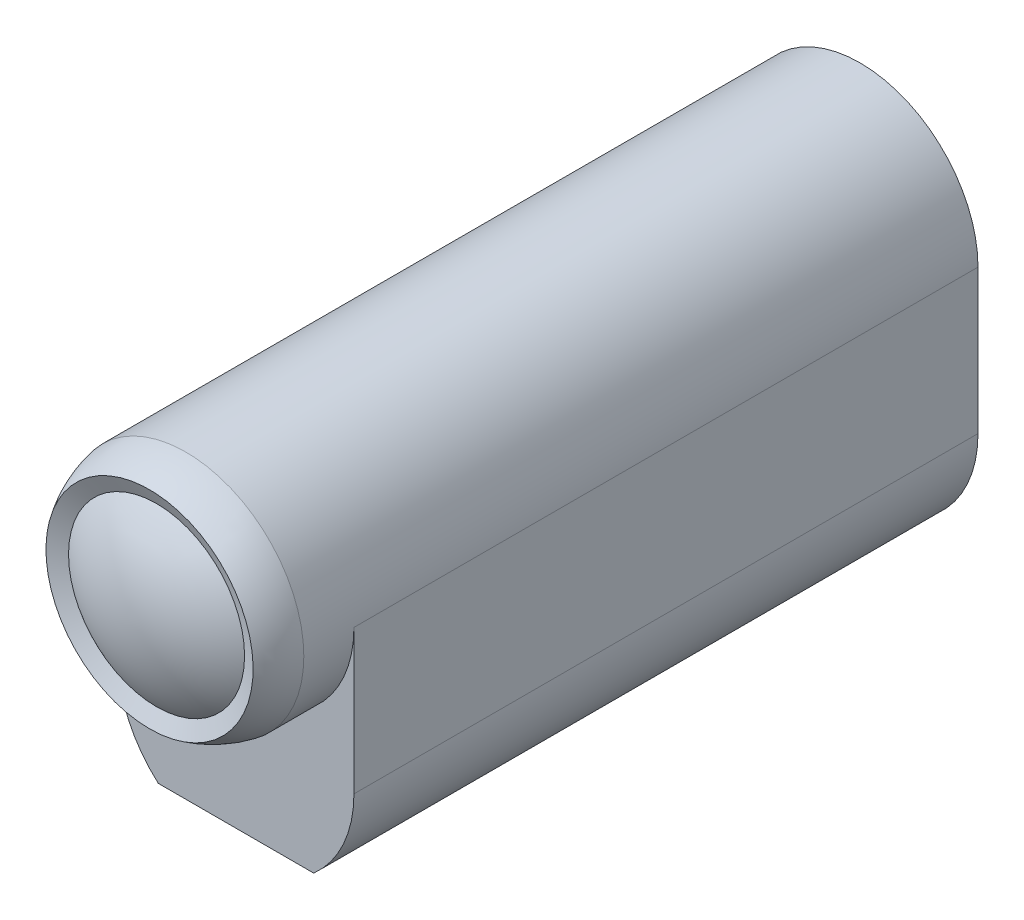
SolidWorks part; units mm, degrees
ref_plane "Front" through (0, 0, 0) normal (0, 0, 1) x (1, 0, 0)
ref_plane "Top" through (0, 0, 0) normal (0, 1, 0) x (1, 0, 0)
ref_plane "Right" through (0, 0, 0) normal (1, 0, 0) x (0, 0, -1)
sketch "Sketch1" plane through (0, 0, 0) normal (0, 0, 1) x (1, 0, 0)
  line L0 (0, 0) -> (0, -36.5673) construction
  line L1 (-7.874, -23.6061) -> (7.874, -23.6061) construction
  line L2 (0, 0) -> (0, 11.9539) construction
  line L3 (-7.874, -23.6061) -> (7.874, -23.6061)
  line L4 (11.9539, 0) -> (11.9539, -14.6119)
  line L5 (-11.9539, 0) -> (-11.9539, -14.6119)
  arc A0 (11.9539, 0) -> (-11.9539, 0) centre (0, 0) ccw
  arc A1 (7.874, -23.6061) -> (11.9539, -14.6119) centre (0, -14.6119) ccw
  arc A2 (-11.9539, -14.6119) -> (-7.874, -23.6061) centre (0, -14.6119) ccw
  dimension "D1" = 23.9078
  dimension "D4" = 35.56
extrude "Boss-Extrude1" add sketch "Sketch1" along normal blind 63.246
sketch "Sketch2" plane through (0, 0, 63.246) normal (0, 0, 1) x (1, 0, 0)
  circle A0 centre (0, 0) radius 11.9539
extrude "Boss-Extrude2" add sketch "Sketch2" along normal blind 5.08
sketch "Sketch3" plane through (0, 0, 0) normal (1, 0, 0) x (0, 0, -1)
  line L0 (-71.2978, 8.9214) -> (-59.3927, 0) construction
  line L1 (-74.2696, 0) -> (-68.326, 0)
  line L3 (-68.326, 11.9539) -> (-68.326, -11.9539) construction
  line L4 (-68.326, 0) -> (-68.326, 11.9539)
  line L5 (-72.009, 10.4976) -> (-71.2978, 8.9214)
  line L7 (-74.2696, 18.018) -> (-74.2696, 0) construction
  line L8 (0, -14.6119) -> (0, 0) construction
  line L9 (-66.6624, 0) -> (-49.6621, 0) construction
  line L10 (-63.246, 0) -> (0, 0) construction
  arc A0 (-68.326, 11.9539) -> (-72.009, 10.4976) centre (-66.6624, 2.361) ccw
  arc A2 (-71.2978, 8.9214) -> (-74.2696, 0) centre (-59.3927, 0) ccw
  dimension "D2" = 14.8769
  dimension "D3" = 9.736
  dimension "D6" = 1.6636
  dimension "D1" = 74.2696
  dimension "D4" = 24.284
  dimension "D5" = 36.847
revolve "Revolve1" add sketch "Sketch3" angle 360 about L1
